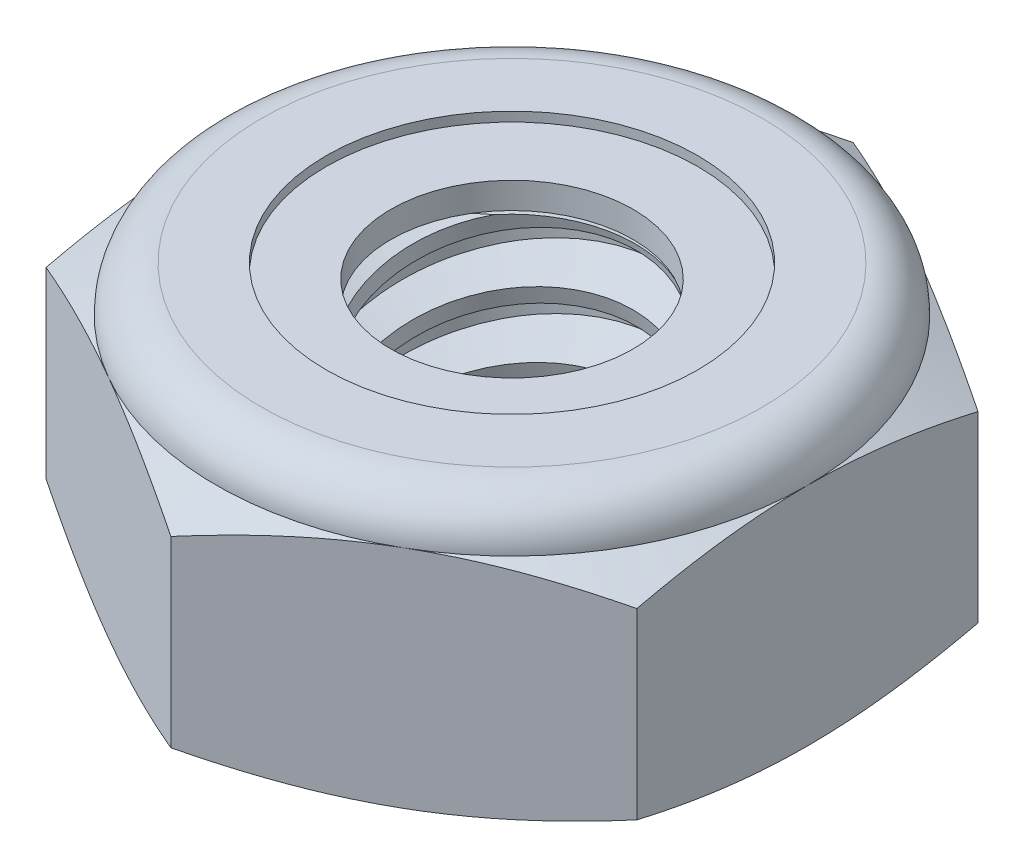
SolidWorks part; units mm, degrees
material "Plain Carbon Steel"
ref_plane "Front" through (0, 0, 0) normal (0, 0, 1) x (1, 0, 0)
ref_plane "Top" through (0, 0, 0) normal (0, 1, 0) x (1, 0, 0)
ref_plane "Right" through (0, 0, 0) normal (1, 0, 0) x (0, 0, -1)
sketch "Sketch1" plane through (0, 0, 0) normal (0, 1, 0) x (1, 0, 0)
  line L1 (0, 5.4993) -> (-4.7625, 2.7496)
  line L2 (-4.7625, 2.7496) -> (-4.7625, -2.7496)
  line L3 (-4.7625, -2.7496) -> (0, -5.4993)
  line L4 (0, -5.4993) -> (4.7625, -2.7496)
  line L5 (4.7625, -2.7496) -> (4.7625, 2.7496)
  line L6 (4.7625, 2.7496) -> (0, 5.4993)
  circle A0 centre (0, 0) radius 4.7625 construction
  dimension "Hex Flats" = 9.525
extrude "Extrude1" add sketch "Sketch1" along normal blind 4.3656
sketch "Sketch2" plane through (0, 0, 0) normal (1, 0, 0) x (0, 0, -1)
  line L0 (-2.413, 0) -> (-2.413, 4.3656) construction
  line L1 (0, 0) -> (2.413, 0)
  line L2 (0, 0) -> (0, 4.3656)
  line L3 (0, 4.3656) -> (2.413, 4.3656)
  line L4 (2.413, 0) -> (2.413, 4.3656)
  line L5 (-2.7496, 4.3656) -> (2.7496, 4.3656) construction
  line L7 (0, -2.413) -> (0, 0) construction
  dimension "Thread Dia" = 4.826
revolve "Revolve1" add sketch "Sketch2" angle 360 about L7
sketch "Sketch3" plane through (0, 0, 0) normal (1, 0, 0) x (0, 0, -1)
  line L0 (2.413, 4.3656) -> (-2.413, 4.3656) construction
  line L1 (-2.413, 4.3656) -> (-2.413, 3.3073) construction
  line L2 (-2.413, 3.3073) -> (2.413, 4.3656) construction
  line L3 (2.413, 4.3656) -> (2.4413, 4.2364) construction
  line L4 (2.4413, 4.2364) -> (2.6397, 3.3319)
  line L5 (2.6397, 3.3319) -> (2.0093, 3.5322)
  line L6 (2.0093, 3.5322) -> (1.9526, 3.7906)
  line L7 (1.9526, 3.7906) -> (2.4413, 4.2364)
  line L8 (1.981, 3.6614) -> (2.5405, 3.7841) construction
  line L9 (2.413, 4.3656) -> (2.413, 3.7562) construction
  line L10 (2.413, 3.7562) -> (-2.413, 2.6978) construction
  line L11 (-2.413, 2.6978) -> (-2.413, 3.3073) construction
  line L12 (-0.2497, 4.3656) -> (0.2497, 2.0884) construction
  line L13 (-2.413, 0) -> (-2.413, 4.3656) construction
  line L14 (0, 4.3656) -> (2.413, 4.3656) construction
  line L15 (2.413, 0) -> (2.413, 4.3656) construction
  point P13 (0, 3.227)
  dimension "D1" = 0.1323
  dimension "D2" = 0.2646
  dimension "Thread Pitch" = 1.0583
  dimension "D4" = 60
  dimension "D5" = 1.0583
revolve "Cut-Revolve1" cut sketch "Sketch3" angle 360 about L12
pattern_linear "LPattern1" count 4 spacing 1.0583 along (0, -1, 0) count 2 spacing 1.0583 along (0, 1, 0) of "Cut-Revolve1"
sketch "Sketch4" plane through (0, 0, 0) normal (1, 0, 0) x (0, 0, -1)
  line L0 (0, 4.3656) -> (2.413, 4.3656)
  line L1 (2.413, 4.3656) -> (1.9526, 4.151)
  line L2 (1.9526, 4.151) -> (1.9526, 0.2147)
  line L3 (1.9526, 0.2147) -> (2.413, 0)
  line L4 (2.413, 0) -> (0, 0)
  line L5 (0, 0) -> (0, 4.3656)
  line L6 (2.413, 0) -> (2.413, 4.3656) construction
  line L7 (0, 4.3656) -> (2.413, 4.3656) construction
  line L8 (0, 0) -> (2.413, 0) construction
  line L9 (0, 0) -> (0, 4.3656) construction
  line L10 (0, 4.3656) -> (0, 4.8736) construction
  dimension "D1" = 25
revolve "Cut-Revolve2" cut sketch "Sketch4" angle 360 about L10
combine bodies "Combine1" operation type subtract main body 112 bodies to subtract 111
sketch "Sketch5" plane through (0, 0, 0) normal (1, 0, 0) x (0, 0, -1)
  line L0 (0, 0) -> (4.7625, 0)
  line L1 (4.7625, 0) -> (5.4993, 0.3436)
  line L2 (5.4993, 0.3436) -> (5.4993, 3.2945)
  line L3 (5.4993, 3.2945) -> (4.7625, 3.638)
  line L4 (4.0349, 4.3656) -> (4.0349, 5.6356)
  line L5 (4.0349, 5.6356) -> (6.7693, 5.6356)
  line L6 (6.7693, 5.6356) -> (6.7693, -1.27)
  line L7 (6.7693, -1.27) -> (0, -1.27)
  line L8 (0, -1.27) -> (0, 0)
  line L9 (4.7625, 3.638) -> (4.7625, 0) construction
  line L10 (0, 0) -> (2.413, 0) construction
  line L13 (5.4993, 1.819) -> (6.7693, 1.819) construction
  line L14 (5.4993, 4.3656) -> (5.4993, 0) construction
  line L15 (0, 0) -> (0, 5.6356) construction
  line L20 (0, 5.6356) -> (4.0349, 5.6356) construction
  line L22 (0, 4.3656) -> (2.413, 4.3656) construction
  arc A0 (4.7625, 3.638) -> (4.0349, 4.3656) centre (4.0349, 3.638) ccw
  dimension "D1" = 25
  dimension "D2" = 1.27
  dimension "D3" = 4.3656
  dimension "D4" = 0.7276
revolve "Cut-Revolve3" cut sketch "Sketch5" angle 360 about L15
sketch "Sketch6" plane through (0, 0, 0) normal (1, 0, 0) x (0, 0, -1)
  line L0 (0, 3.638) -> (4.6101, 3.638)
  line L1 (4.0349, 4.2132) -> (2.9938, 4.2132)
  line L2 (0, 5.6356) -> (0, 3.638)
  line L3 (2.9938, 5.6356) -> (0, 5.6356)
  line L4 (0, 5.6356) -> (4.0349, 5.6356) construction
  line L5 (0, 0) -> (0, 5.6356) construction
  line L6 (0, 5.6356) -> (0, 44.323) construction
  line L7 (2.9938, 4.2132) -> (2.9938, 5.6356)
  line L8 (4.0349, 4.3656) -> (4.0349, 4.2132) construction
  line L9 (2.9938, 4.2132) -> (1.9526, 4.2132) construction
  line L10 (1.9526, 4.2132) -> (1.9526, 4.151) construction
  arc A0 (4.6101, 3.638) -> (4.0349, 4.2132) centre (4.0349, 3.638) ccw
  arc A1 (4.7625, 3.638) -> (4.0349, 4.3656) centre (4.0349, 3.638) ccw construction
  dimension "D1" = 0.1524
revolve "Cut-Revolve4" cut sketch "Sketch6" angle 360 about L6
sketch "Sketch7" plane through (0, 0, 0) normal (1, 0, 0) x (0, 0, -1)
  line L0 (1.9526, 3.7142) -> (4.528, 3.7142)
  line L1 (4.0349, 4.137) -> (1.9526, 4.137)
  line L2 (1.9526, 4.137) -> (1.9526, 3.7142)
  line L3 (1.9526, 3.7142) -> (0, 3.7142) construction
  line L4 (0, 3.7142) -> (0, 4.137) construction
  line L5 (0, 4.137) -> (1.9526, 4.137) construction
  line L6 (1.9526, 3.7142) -> (1.9526, 3.638) construction
  line L7 (0, 3.638) -> (4.6101, 3.638) construction
  line L8 (4.0349, 4.137) -> (4.0349, 4.2132) construction
  arc A0 (4.528, 3.7142) -> (4.0349, 4.137) centre (4.0349, 3.638) ccw
  arc A2 (4.6101, 3.638) -> (4.0349, 4.2132) centre (4.0349, 3.638) ccw construction
  dimension "D1" = 0.0762
revolve "Revolve2" add sketch "Sketch7" angle 360 about L4
equation "\"D1@Sketch3\"=\"Thread Pitch@Sketch3\"/8"
equation "\"D2@Sketch3\"=\"Thread Pitch@Sketch3\"/4"
equation "\"D5@Sketch3\"=\"Thread Pitch@Sketch3\""
equation "\"D4@LPattern1\"=\"Thread Pitch@Sketch3\""
equation "\"D3@LPattern1\"=\"Thread Pitch@Sketch3\""
equation "\"D1@LPattern1\"=\"Height@Extrude1\"/\"Thread Pitch@Sketch3\""
equation "\"D4@Sketch5\"=\"Height@Extrude1\"/6"
